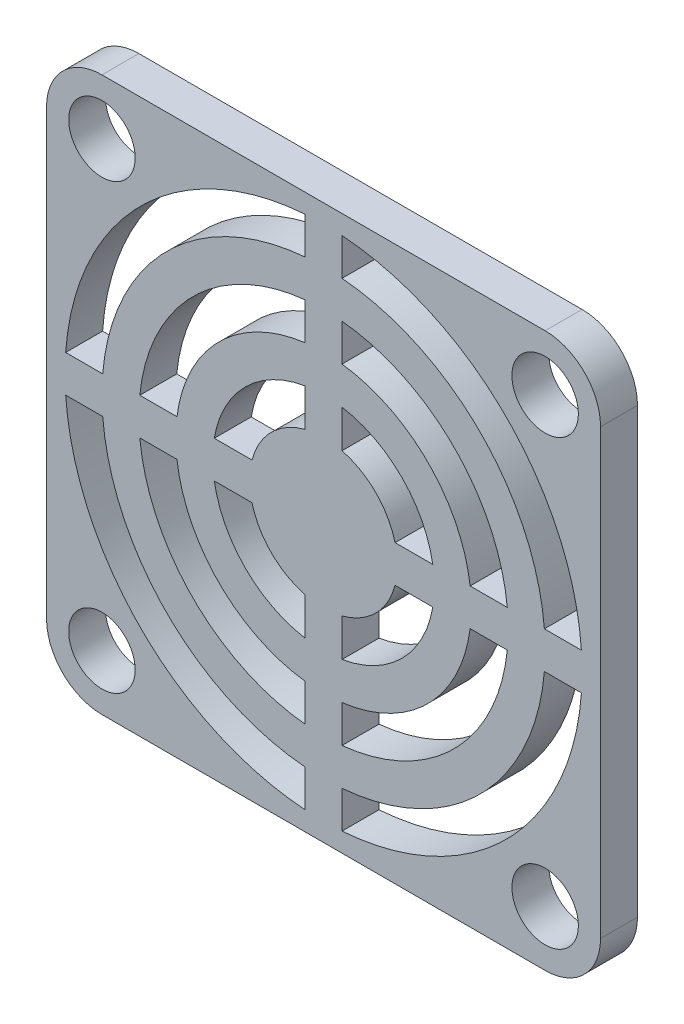
SolidWorks part; units mm, degrees
material "ABS"
ref_plane "Front Plane" through (0, 0, 0) normal (0, 0, 1) x (1, 0, 0)
ref_plane "Top Plane" through (0, 0, 0) normal (0, 1, 0) x (1, 0, 0)
ref_plane "Right Plane" through (0, 0, 0) normal (1, 0, 0) x (0, 0, -1)
sketch "Sketch1" plane through (0, 0, 0) normal (0, 0, 1) x (1, 0, 0)
  line L1 (-15, -15) -> (15, -15)
  line L2 (-15, -15) -> (-15, 15)
  line L3 (-15, 15) -> (15, 15)
  line L4 (15, -15) -> (15, 15)
  line L5 (-15, -15) -> (15, 15) construction
  line L6 (-15, 15) -> (15, -15) construction
  point P0 (0, 0)
  dimension "D1" = 30
extrude "Boss-Extrude1" add sketch "Sketch1" along normal blind 2
sketch "Sketch2" plane through (0, 0, 2) normal (0, 0, 1) x (1, 0, 0)
  line L1 (-12, 12) -> (12, 12) construction
  line L2 (12, 12) -> (12, -12) construction
  line L3 (12, -12) -> (-12, 12) construction
  circle A0 centre (-12, 12) radius 1.8
  circle A1 centre (12, 12) radius 1.8
  circle A2 centre (12, -12) radius 1.8
  circle A3 centre (-12, -12) radius 1.8
  dimension "D2" = 3.6
  dimension "D1" = 24
extrude "Cut-Extrude1" cut sketch "Sketch2" against normal through all
fillet "Fillet1" radius 3 4 edges at (15, -15, 1) (-15, -15, 1) (15, 15, 1) (-15, 15, 1)
sketch "Sketch3" plane through (0, 0, 2) normal (0, 0, 1) x (1, 0, 0)
  line L4 (0, 0) -> (0, 14) construction
  line L5 (0, 0) -> (14, 0) construction
  line L6 (0, 0) -> (0, -14) construction
  line L7 (0, 0) -> (-14, 0) construction
  line L8 (-7.9373, 1) -> (-9.9499, 1)
  line L9 (-1, -3.873) -> (-1, -5.9161)
  line L10 (-3.873, 1) -> (-5.9161, 1)
  line L11 (3.873, -1) -> (5.9161, -1)
  line L12 (-1, 3.873) -> (-1, 5.9161)
  line L13 (1, -3.873) -> (1, -5.9161)
  line L14 (-3.873, -1) -> (-5.9161, -1)
  line L15 (3.873, 1) -> (5.9161, 1)
  line L16 (-1, 0) -> (-1, 14) construction
  line L17 (-11.9583, 1) -> (-13.9642, 1)
  line L18 (0, 1) -> (-14, 1) construction
  line L19 (0, -1) -> (-14, -1) construction
  line L20 (-1, 0) -> (-1, -14) construction
  line L21 (1, 0) -> (1, -14) construction
  line L22 (0, -1) -> (14, -1) construction
  line L23 (0, 1) -> (14, 1) construction
  line L24 (1, 3.873) -> (1, 5.9161)
  line L25 (-1, 11.9583) -> (-1, 13.9642)
  line L26 (1, 11.9583) -> (1, 13.9642)
  line L27 (1, 7.9373) -> (1, 9.9499)
  line L28 (-1, 7.9373) -> (-1, 9.9499)
  line L29 (7.9373, 1) -> (9.9499, 1)
  line L30 (7.9373, -1) -> (9.9499, -1)
  line L31 (11.9583, 1) -> (13.9642, 1)
  line L32 (11.9583, -1) -> (13.9642, -1)
  line L33 (1, -11.9583) -> (1, -13.9642)
  line L34 (-1, -11.9583) -> (-1, -13.9642)
  line L35 (-1, -7.9373) -> (-1, -9.9499)
  line L36 (1, -7.9373) -> (1, -9.9499)
  line L37 (-11.9583, -1) -> (-13.9642, -1)
  line L38 (-7.9373, -1) -> (-9.9499, -1)
  arc A0 (-1, 5.9161) -> (-5.9161, 1) centre (0, 0) ccw
  arc A1 (-1, 9.9499) -> (-9.9499, 1) centre (0, 0) ccw
  arc A2 (-1, 13.9642) -> (-13.9642, 1) centre (0, 0) ccw
  arc A3 (-1, 11.9583) -> (-11.9583, 1) centre (0, 0) ccw
  arc A4 (-1, 7.9373) -> (-7.9373, 1) centre (0, 0) ccw
  arc A9 (-1, 3.873) -> (-3.873, 1) centre (0, 0) ccw
  circle A10 centre (0, 0) radius 4 construction
  circle A11 centre (0, 0) radius 6 construction
  circle A12 centre (0, 0) radius 8 construction
  circle A13 centre (0, 0) radius 10 construction
  circle A14 centre (0, 0) radius 12 construction
  circle A15 centre (0, 0) radius 14 construction
  arc A16 (-13.9642, -1) -> (-1, -13.9642) centre (0, 0) ccw
  arc A17 (-11.9583, -1) -> (-1, -11.9583) centre (0, 0) ccw
  arc A18 (-9.9499, -1) -> (-1, -9.9499) centre (0, 0) ccw
  arc A19 (-7.9373, -1) -> (-1, -7.9373) centre (0, 0) ccw
  arc A20 (-5.9161, -1) -> (-1, -5.9161) centre (0, 0) ccw
  arc A21 (-3.873, -1) -> (-1, -3.873) centre (0, 0) ccw
  arc A22 (3.873, 1) -> (1, 3.873) centre (0, 0) ccw
  arc A23 (5.9161, 1) -> (1, 5.9161) centre (0, 0) ccw
  arc A24 (7.9373, 1) -> (1, 7.9373) centre (0, 0) ccw
  arc A25 (9.9499, 1) -> (1, 9.9499) centre (0, 0) ccw
  arc A26 (11.9583, 1) -> (1, 11.9583) centre (0, 0) ccw
  arc A27 (13.9642, 1) -> (1, 13.9642) centre (0, 0) ccw
  arc A28 (1, -3.873) -> (3.873, -1) centre (0, 0) ccw
  arc A29 (1, -5.9161) -> (5.9161, -1) centre (0, 0) ccw
  arc A30 (1, -7.9373) -> (7.9373, -1) centre (0, 0) ccw
  arc A31 (1, -9.9499) -> (9.9499, -1) centre (0, 0) ccw
  arc A32 (1, -11.9583) -> (11.9583, -1) centre (0, 0) ccw
  arc A33 (1, -13.9642) -> (13.9642, -1) centre (0, 0) ccw
  dimension "D1" = 28
  dimension "D2" = 20
  dimension "D3" = 12
  dimension "D9" = 1
  dimension "D4" = 2
  dimension "D5" = 2
  dimension "D6" = 1
  dimension "D7" = 2
  dimension "D8" = 1
extrude "Cut-Extrude2" cut sketch "Sketch3" against normal through all
